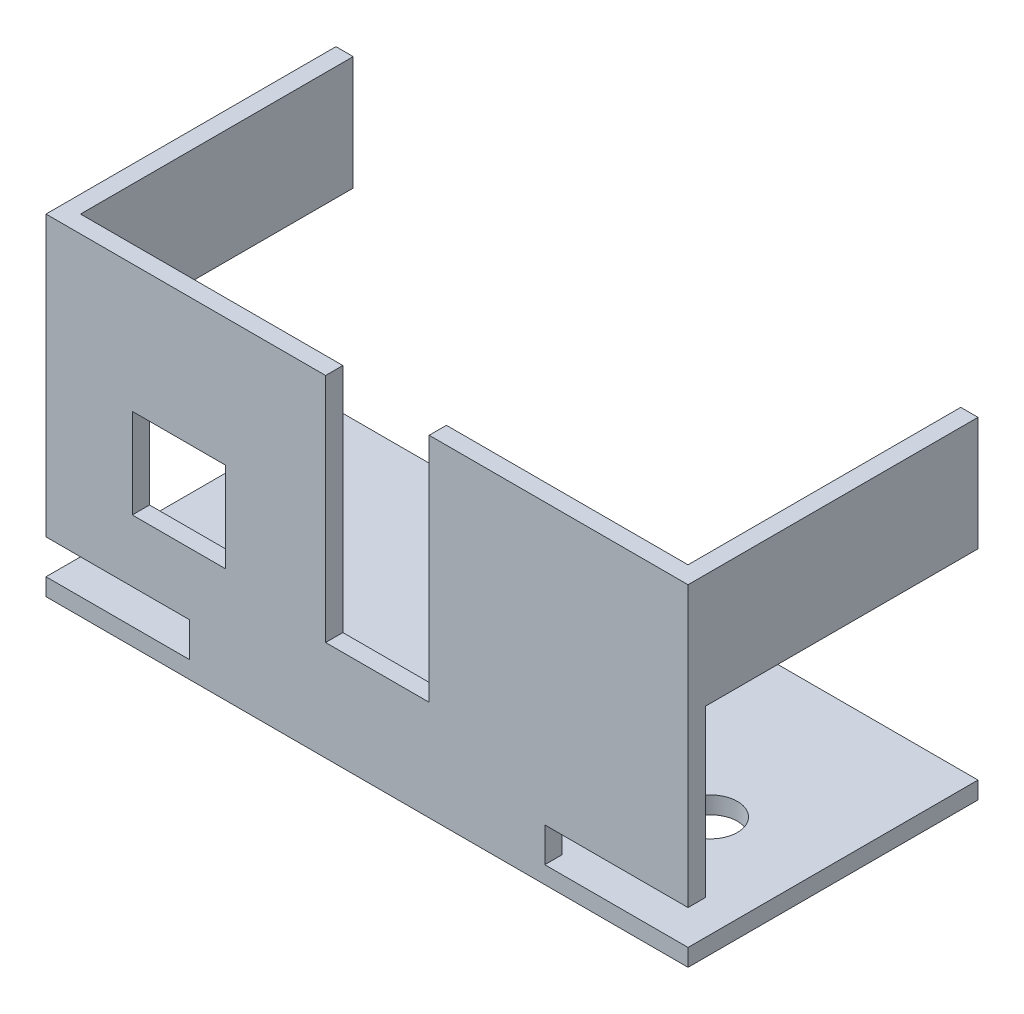
SolidWorks part; units mm, degrees
ref_plane "Front" through (0, 0, 0) normal (0, 0, 1) x (1, 0, 0)
ref_plane "Top" through (0, 0, 0) normal (0, 1, 0) x (1, 0, 0)
ref_plane "Right" through (0, 0, 0) normal (1, 0, 0) x (0, 0, -1)
sketch "Sketch1" plane through (0, 0, 0) normal (0, 0, 1) x (1, 0, 0)
  line L0 (-1.25, 0) -> (-1.25, 24)
  line L1 (-1.25, 0) -> (45.25, 0)
  line L2 (0, 0) -> (0, 22.75) construction
  line L3 (-1.25, 22.75) -> (45.25, 22.75) construction
  line L4 (44, 0) -> (44, 22.75) construction
  line L5 (45.25, 0) -> (45.25, 24)
  line L6 (-1.25, 24) -> (45.25, 24)
  line L7 (-1.25, 0) -> (-1.25, 22.75) construction
  line L8 (45.25, 0) -> (45.25, 22.75) construction
  dimension "D1" = 44
  dimension "D2" = 22.75
  dimension "D5" = 46.5
  dimension "D3" = 1.25
  dimension "D4" = 1.25
  dimension "D6" = 1.25
extrude "Boss-Extrude1" add sketch "Sketch1" against normal blind 21
shell "Shell1" thickness 1.25
sketch "Sketch2" plane through (-1.25, 0, 0) normal (-1, 0, 0) x (0, 0, 1)
  line L0 (-1.25, 24) -> (-1.25, 1.25) construction
  line L1 (-21, 1.25) -> (-1.25, 1.25)
  line L2 (-21, 1.25) -> (-21, 15.75)
  line L3 (-21, 15.75) -> (-1.25, 15.75)
  line L4 (-1.25, 1.25) -> (-1.25, 15.75)
  dimension "D1" = 14.5
extrude "Cut-Extrude1" cut sketch "Sketch2" against normal through all
sketch "Sketch4" plane through (0, 0, 0) normal (0, 0, 1) x (1, 0, 0)
  line L0 (-1.25, 1.25) -> (45.25, 1.25) construction
  line L1 (5, 14.75) -> (11.75, 14.75)
  line L2 (5, 14.75) -> (5, 8.25)
  line L3 (5, 8.25) -> (11.75, 8.25)
  line L4 (11.75, 14.75) -> (11.75, 8.25)
  line L5 (19, 24.25) -> (26.5, 24.25)
  line L6 (19, 24.25) -> (19, 7.25)
  line L7 (19, 7.25) -> (26.5, 7.25)
  line L8 (26.5, 24.25) -> (26.5, 7.25)
  line L11 (0, 24) -> (0, 15.75) construction
  dimension "D1" = 7
  dimension "D2" = 6
  dimension "D3" = 13.5
  dimension "D4" = 6.5
  dimension "D5" = 11.75
  dimension "D6" = 5
  dimension "D7" = 6.75
  dimension "D8" = 19
  dimension "D9" = 26.5
  dimension "D10" = 7.5
  dimension "D11" = 23
  dimension "D12" = 17
extrude "Cut-Extrude3" cut sketch "Sketch4" against normal up to surface (1.25 mm away) up to face at (22, 14.1875, -1.25)
sketch "Sketch6" plane through (0, 0, 0) normal (0, -1, 0) x (-1, 0, 0)
  line L0 (1.25, 0) -> (-45.25, 0) construction
  line L1 (-22, 0) -> (-22, 5.6918) construction
  circle A0 centre (-37.875, 9) radius 1.95
  circle A1 centre (-6.125, 9) radius 1.95
  dimension "D1" = 3.9
  dimension "D2" = 9
  dimension "D3" = 31.75
extrude "Cut-Extrude4" cut sketch "Sketch6" against normal up to surface (1.25 mm away) contours A1 | A0
sketch "Sketch7" plane through (0, 0, 0) normal (0, 0, 1) x (1, 0, 0)
  line L0 (45.25, 0) -> (45.25, 24) construction
  line L1 (45.25, 1.25) -> (34.875, 1.25)
  line L2 (45.25, 1.25) -> (45.25, 3.75)
  line L3 (45.25, 3.75) -> (34.875, 3.75)
  line L4 (34.875, 1.25) -> (34.875, 3.75)
  line L5 (-1.25, 0) -> (45.25, 0) construction
  line L6 (35.925, 0) -> (39.825, 0) construction
  line L7 (35.925, 0) -> (39.825, 0) construction
  line L8 (37.875, 0) -> (37.875, 1.5787) construction
  line L9 (22, 0) -> (22, 4.652) construction
  line L10 (9.125, 1.25) -> (9.125, 3.75)
  line L11 (-1.25, 3.75) -> (9.125, 3.75)
  line L12 (-1.25, 1.25) -> (-1.25, 3.75)
  line L13 (-1.25, 1.25) -> (9.125, 1.25)
  dimension "D1" = 1.25
  dimension "D2" = 3
  dimension "D3" = 2.5
extrude "Cut-Extrude5" cut sketch "Sketch7" against normal up to surface (1.25 mm away) up to face at (22.25, 14.6667, -1.25)
